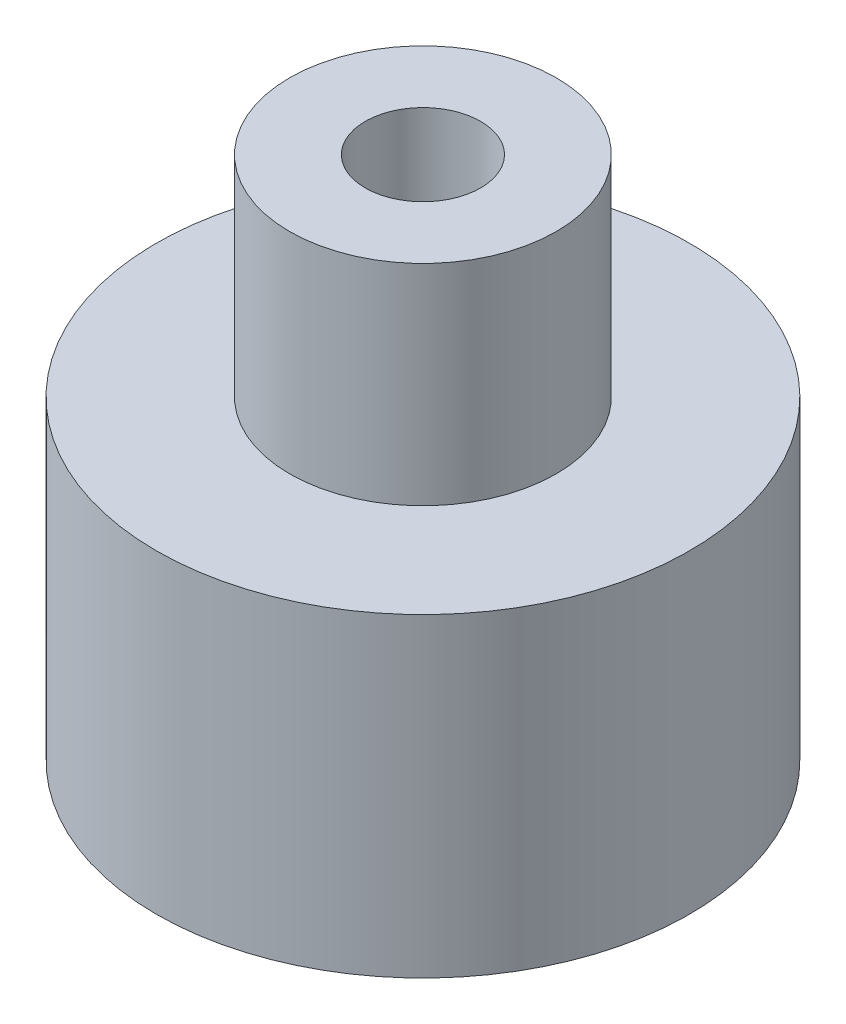
SolidWorks part; units mm, degrees
ref_plane "Alzado" through (0, 0, 0) normal (0, 0, 1) x (1, 0, 0)
ref_plane "Planta" through (0, 0, 0) normal (0, 1, 0) x (1, 0, 0)
ref_plane "Vista lateral" through (0, 0, 0) normal (1, 0, 0) x (0, 0, -1)
sketch "Croquis1" plane through (0, 0, 0) normal (0, 0, 1) x (1, 0, 0)
  line L0 (0, 50) -> (0, 0)
  line L1 (0, 0) -> (25.4, 0)
  line L2 (25.4, 0) -> (25.4, 30)
  line L3 (25.4, 30) -> (12.7, 30)
  line L4 (12.7, 30) -> (12.7, 50)
  line L5 (12.7, 50) -> (0, 50)
  point P3 (0, 0)
  dimension "D1" = 50
  dimension "D2" = 20
  dimension "D3" = 25.4
  dimension "D4" = 12.7
revolve "Revolución1" add sketch "Croquis1" angle 360 about L0
hole_wizard "Refrentado para tornillo con cabeza hueca de M61" positions "Croquis2" profile "Croquis3" counterbore size "M6" standard "DIN" end condition through all
sketch "Croquis2" plane through (0, 50, 0) normal (0, 1, 0) x (1, 0, 0)
  point P0 (0, 0)
sketch "Croquis3" plane through (0, 50, 0) normal (1, 0, 0) x (0, 0, 1)
  line L0 (0, 0) -> (0, 50)
  line L1 (0, 50) -> (3.3, 50)
  line L3 (3.3, 50) -> (3.3, 36.4)
  line L4 (3.3, 36.4) -> (5.5, 36.4)
  line L5 (5.5, 36.4) -> (5.5, 0)
  line L7 (5.5, 0) -> (0, 0)
  line L11 (0, -6.35) -> (0, 107.95) construction
  dimension "Diámetro de taladro hasta el siguiente" = 6.6
  dimension "Profundidad de taladro hasta el siguiente" = 50
  dimension "Diámetro de refrentado" = 11
  dimension "Profundidad de refrentado" = 36.4
